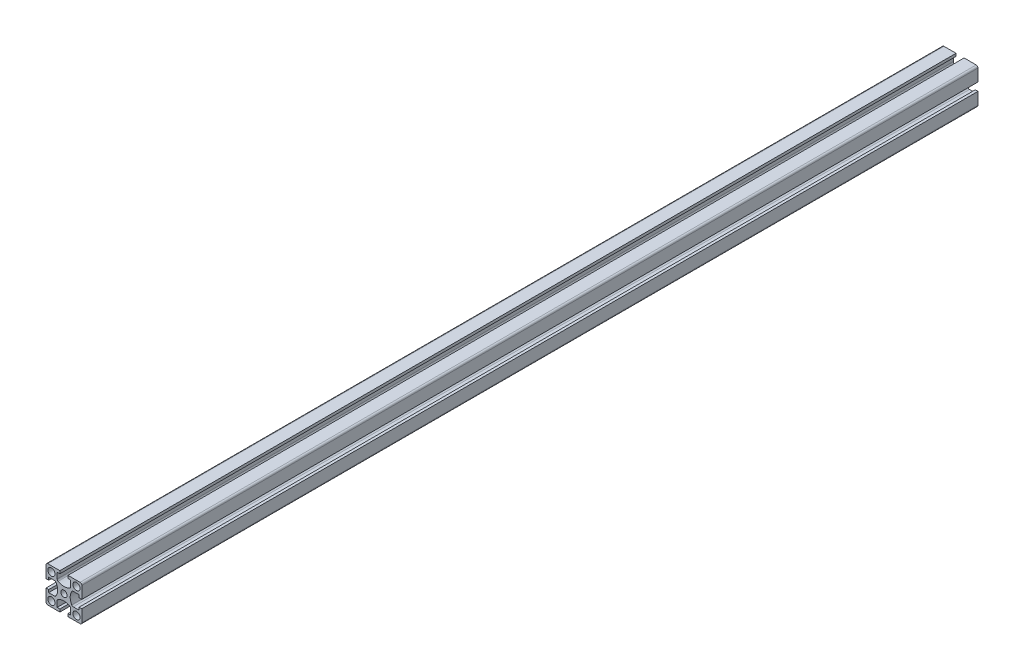
SolidWorks part; units mm, degrees
ref_plane "Front Plane" through (0, 0, 0) normal (0, 0, 1) x (1, 0, 0)
ref_plane "Top Plane" through (0, 0, 0) normal (0, 1, 0) x (1, 0, 0)
ref_plane "Right Plane" through (0, 0, 0) normal (1, 0, 0) x (0, 0, -1)
sketch "Sketch1" plane through (0, 0, 0) normal (0, 0, 1) x (1, 0, 0)
  line L64 (-20, 18) -> (-20, 4.5)
  line L65 (-20, 4.5) -> (-17, 4.5)
  line L66 (-17, 4.5) -> (-17, 7.5)
  line L67 (-17, 7.5) -> (-10.4737, 7.5)
  line L68 (-10.4737, -7.5) -> (-17, -7.5)
  line L69 (-17, -7.5) -> (-17, -4.5)
  line L70 (-17, -4.5) -> (-20, -4.5)
  line L71 (-20, -4.5) -> (-20, -18)
  line L72 (-18, -20) -> (-4.5, -20)
  line L73 (-4.5, -20) -> (-4.5, -17)
  line L74 (-4.5, -17) -> (-7.5, -17)
  line L75 (-7.5, -17) -> (-7.5, -10.4737)
  line L76 (7.5, -10.4737) -> (7.5, -17)
  line L77 (7.5, -17) -> (4.5, -17)
  line L78 (4.5, -17) -> (4.5, -20)
  line L79 (4.5, -20) -> (18, -20)
  line L80 (20, -18) -> (20, -4.5)
  line L81 (20, -4.5) -> (17, -4.5)
  line L82 (17, -4.5) -> (17, -7.5)
  line L83 (17, -7.5) -> (10.4737, -7.5)
  line L84 (10.4737, 7.5) -> (17, 7.5)
  line L85 (17, 7.5) -> (17, 4.5)
  line L86 (17, 4.5) -> (20, 4.5)
  line L87 (20, 4.5) -> (20, 18)
  line L88 (18, 20) -> (4.5, 20)
  line L89 (4.5, 20) -> (4.5, 17)
  line L90 (4.5, 17) -> (7.5, 17)
  line L91 (7.5, 17) -> (7.5, 10.4737)
  line L92 (-7.5, 10.4737) -> (-7.5, 17)
  line L93 (-7.5, 17) -> (-4.5, 17)
  line L94 (-4.5, 17) -> (-4.5, 20)
  line L95 (-4.5, 20) -> (-18, 20)
  circle A5 centre (-14, -14) radius 4
  circle A6 centre (14, -14) radius 4
  circle A7 centre (14, 14) radius 4
  circle A8 centre (0, 0) radius 3.5
  circle A9 centre (-14, 14) radius 4
  arc A32 (-18, 20) -> (-20, 18) centre (-18, 18) ccw
  arc A33 (-8.7417, 6.5) -> (-10.4737, 7.5) centre (-10.4737, 5.5) ccw
  arc A34 (-8.7417, -6.5) -> (-8.7417, 6.5) centre (-20, 0) ccw
  arc A35 (-10.4737, -7.5) -> (-8.7417, -6.5) centre (-10.4737, -5.5) ccw
  arc A36 (-20, -18) -> (-18, -20) centre (-18, -18) ccw
  arc A37 (-6.5, -8.7417) -> (-7.5, -10.4737) centre (-5.5, -10.4737) ccw
  arc A38 (6.5, -8.7417) -> (-6.5, -8.7417) centre (0, -20) ccw
  arc A39 (7.5, -10.4737) -> (6.5, -8.7417) centre (5.5, -10.4737) ccw
  arc A40 (18, -20) -> (20, -18) centre (18, -18) ccw
  arc A41 (8.7417, -6.5) -> (10.4737, -7.5) centre (10.4737, -5.5) ccw
  arc A42 (8.7417, 6.5) -> (8.7417, -6.5) centre (20, 0) ccw
  arc A43 (10.4737, 7.5) -> (8.7417, 6.5) centre (10.4737, 5.5) ccw
  arc A44 (20, 18) -> (18, 20) centre (18, 18) ccw
  arc A45 (6.5, 8.7417) -> (7.5, 10.4737) centre (5.5, 10.4737) ccw
  arc A46 (-6.5, 8.7417) -> (6.5, 8.7417) centre (0, 20) ccw
  arc A47 (-7.5, 10.4737) -> (-6.5, 8.7417) centre (-5.5, 10.4737) ccw
extrude "Boss-Extrude1" add sketch "Sketch1" along normal blind 1000
